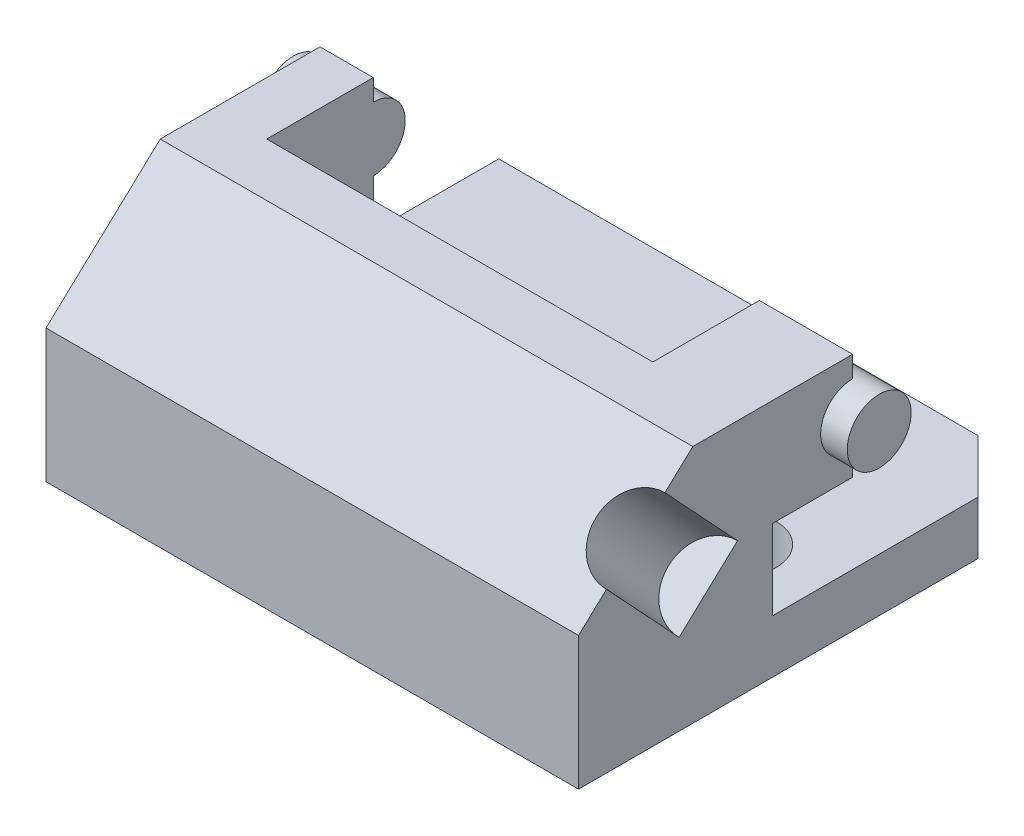
SolidWorks part; units mm, degrees
material "Alliage 1060"
ref_plane "Plan de face" through (0, 0, 0) normal (0, 0, 1) x (1, 0, 0)
ref_plane "Plan de dessus" through (0, 0, 0) normal (0, 1, 0) x (1, 0, 0)
ref_plane "Plan de droite" through (0, 0, 0) normal (1, 0, 0) x (0, 0, -1)
sketch "Esquisse1" plane through (0, 0, 0) normal (1, 0, 0) x (0, 0, -1)
  line L0 (0, 0) -> (48.5526, 0)
  line L1 (48.5526, 0) -> (48.5526, -10)
  line L2 (48.5526, -10) -> (-36.4474, -10)
  line L3 (-36.4474, -10) -> (-36.4474, 15)
  line L4 (-36.4474, 15) -> (-15, 35)
  line L5 (-15, 35) -> (15, 35)
  line L6 (0, 0) -> (0, 15)
  line L7 (0, 15) -> (15, 15)
  line L8 (15, 15) -> (15, 19)
  line L9 (15, 35) -> (15, 31) construction
  line L10 (21, 25) -> (34.0027, 25) construction
  line L11 (15, 31) -> (15, 35)
  circle A0 centre (15, 25) radius 6
  point P7 (48.5526, -5)
  dimension "D1" = 85
  dimension "D2" = 10
  dimension "D3" = 15
  dimension "D4" = 20
  dimension "D6" = 30
  dimension "D5" = 20
  dimension "D7" = 47
  dimension "D8" = 15
extrude "Boss.-Extru.1" add sketch "Esquisse1" along normal blind 100 contours A0 L11 L5 L4 L3 L2 L1 L0 L6 L7 L8 | A0
sketch "Esquisse2" plane through (100, 0, 0) normal (1, 0, 0) x (0, 0, -1)
  circle A0 centre (15, 25) radius 6
extrude "Boss.-Extru.2" add sketch "Esquisse2" along normal blind 5
sketch "Esquisse3" plane through (0, 0, 0) normal (-1, 0, 0) x (0, 0, 1)
  circle A0 centre (-15, 25) radius 6
extrude "Boss.-Extru.3" add sketch "Esquisse3" along normal blind 5
sketch "Esquisse4" plane through (0, 26.2025, 24.4342) normal (0, 0.7314, 0.682) x (1, 0, 0)
  line L0 (100, -16.4259) -> (100, 12.8996) construction
  line L1 (100, 12.8996) -> (100, -1.7632)
  circle A0 centre (100, -1.7632) radius 7.5
  line M3 (100, -16.4259) -> (100, 12.8996)
extrude "Enlèv. mat.-Extru.1" cut sketch "Esquisse4" against normal blind 20 contours A0 M3
sketch "Esquisse5" plane through (0, 35, 0) normal (0, 1, 0) x (1, 0, 0)
  line L0 (0, 15) -> (10, 15)
  line L1 (10, 15) -> (10, -5)
  line L2 (10, -5) -> (82.5, -5)
  line L3 (82.5, -5) -> (82.5, 21)
  line L4 (105, 21) -> (-5, 21) construction
  line L6 (10, 21) -> (10, 15)
  line L7 (0, -15) -> (0, 15) construction
  line L8 (10, 21) -> (10, 25.1377)
  line L9 (10, 25.1377) -> (82.5, 25.1377)
  line L10 (82.5, 25.1377) -> (82.5, 21)
  line L11 (100, -15) -> (0, -15) construction
  line M9 (100, 15) -> (0, 15)
  dimension "D1" = 72.5
  dimension "D2" = 10
  dimension "D3" = 10
extrude "Enlèv. mat.-Extru.3" cut sketch "Esquisse5" against normal up to surface (35 mm away) contours L2 L3 L1 M9 up to face at (50, 0, -24.2763)
sketch "Esquisse6" plane through (0, 0, 0) normal (0, 1, 0) x (1, 0, 0)
  line L0 (10, 15) -> (10, 21)
  line L1 (105, 21) -> (-5, 21) construction
  line L2 (82.5, 15) -> (82.5, 21)
  line L3 (82.5, 21) -> (10, 21)
  line L4 (10, 15) -> (82.5, 15)
extrude "Enlèv. mat.-Extru.4" cut sketch "Esquisse6" along normal blind 40
sketch "Esquisse7" plane through (0, -10, 0) normal (0, -1, 0) x (1, 0, 0)
  line L0 (0, -48.5526) -> (0, -8.149)
  line L1 (0, -48.5526) -> (0, 36.4474) construction
  line L2 (0, -8.149) -> (15, -8.149)
  line L3 (15, -8.149) -> (35, -8.149)
  line L4 (35, -8.149) -> (65, -8.149)
  line L5 (65, -8.149) -> (85, -8.149)
  line L6 (85, -8.149) -> (100, -8.149)
  line L7 (100, -48.5526) -> (100, 36.4474) construction
  line L8 (35, -8.149) -> (65, -8.149) construction
  line L9 (35, -0.649) -> (65, -0.649)
  line L10 (35, -15.649) -> (65, -15.649)
  circle A0 centre (15, -8.149) radius 7.5
  circle A1 centre (85, -8.149) radius 7.5
  arc A2 (35, -0.649) -> (35, -15.649) centre (35, -8.149) ccw
  arc A3 (65, -15.649) -> (65, -0.649) centre (65, -8.149) ccw
  point P14 (50, -8.149)
extrude "Enlèv. mat.-Extru.5" cut sketch "Esquisse7" against normal blind 10 contours L3 A0 L2 | L2 A0 L3 | L5 A3 L9 A2 L3 L4 | L10 A3 L5 L4 L3 A2 | L6 A1 L5 | L5 A1 L6
sketch "Esquisse8" plane through (0, -10, 0) normal (0, -1, 0) x (1, 0, 0)
  line L0 (100, -48.5526) -> (100, -38.5526)
  line L1 (100, -48.5526) -> (100, 36.4474) construction
  line L2 (100, -38.5526) -> (90, -48.5526)
  line L3 (100, -48.5526) -> (0, -48.5526) construction
  line L4 (90, -48.5526) -> (100, -48.5526)
  dimension "D1" = 10
  dimension "D2" = 45
extrude "Enlèv. mat.-Extru.6" cut sketch "Esquisse8" against normal blind 10
equation "\"A\" = 85"
equation "\"B\" = 72.5"
equation "\"C\"= 47"
equation "\"D1@Esquisse1\"=\"A\""
equation "\"D7@Esquisse1\"=\"C\""
equation "\"D1@Esquisse5\"=\"B\""
